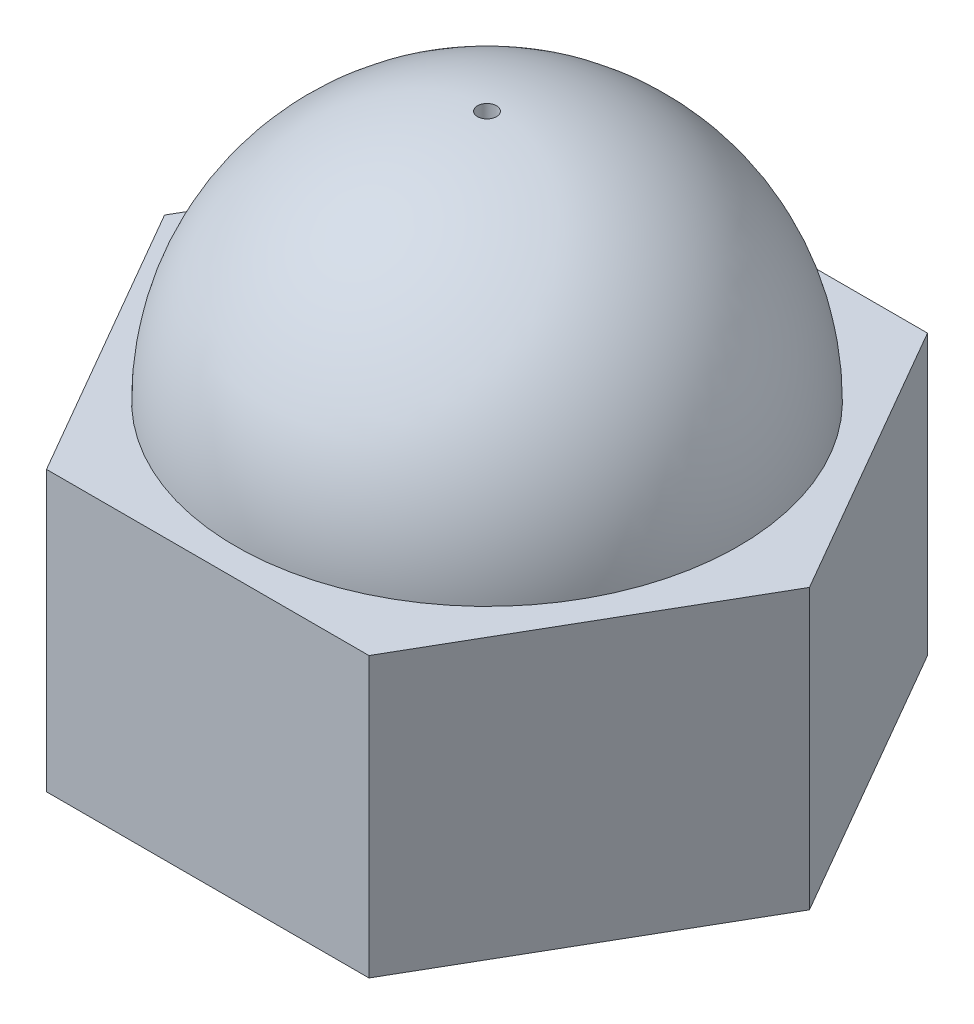
SolidWorks part; units mm, degrees
material "Brass"
ref_plane "Front Plane" through (0, 0, 0) normal (0, 0, 1) x (1, 0, 0)
ref_plane "Top Plane" through (0, 0, 0) normal (0, 1, 0) x (1, 0, 0)
ref_plane "Right Plane" through (0, 0, 0) normal (1, 0, 0) x (0, 0, -1)
ref_axis "Axis1" through (0, 0, 0) along (0, 1, 0)
sketch "Sketch1" plane through (0, 0, 0) normal (0, 1, 0) x (1, 0, 0)
  line L1 (5.7735, 0) -> (2.8868, 5)
  line L2 (2.8868, 5) -> (-2.8868, 5)
  line L3 (-2.8868, 5) -> (-5.7735, 0)
  line L4 (-5.7735, 0) -> (-2.8868, -5)
  line L5 (-2.8868, -5) -> (2.8868, -5)
  line L6 (2.8868, -5) -> (5.7735, 0)
  circle A0 centre (0, 0) radius 5 construction
  dimension "D1" = 10
extrude "Boss-Extrude1" add sketch "Sketch1" along normal blind 5
sketch "Sketch3" plane through (0, 0, 0) normal (0, 0, 1) x (1, 0, 0)
  line L0 (0, 5) -> (-4.5, 5)
  line L1 (0, 9.5) -> (0, 5)
  line L2 (0, 0) -> (0, 5.5449) construction
  arc A0 (-4.5, 5) -> (0, 9.5) centre (0, 5) cw
  dimension "D1" = 4.5
revolve "Revolve1" add sketch "Sketch3" angle 360 about axis through (0, 0, 0) along (0, 1, 0)
sketch "Sketch4" plane through (0, 0, 0) normal (0, -1, 0) x (1, 0, 0)
  circle A0 centre (0, 0) radius 3
  dimension "D1" = 6
extrude "Cut-Extrude1" cut sketch "Sketch4" against normal blind 5
sketch "Sketch6" plane through (0, 5, 0) normal (0, -1, 0) x (1, 0, 0)
  circle A0 centre (0, 0) radius 0.17
  dimension "D1" = 0.34
extrude "Cut-Extrude2" cut sketch "Sketch6" against normal through all
chamfer "Chamfer1" [suppressed] distance 1.5 distance2 2
chamfer "Chamfer2" distance 0.875 distance2 2 1 edges at (0, 5, -0.17)
